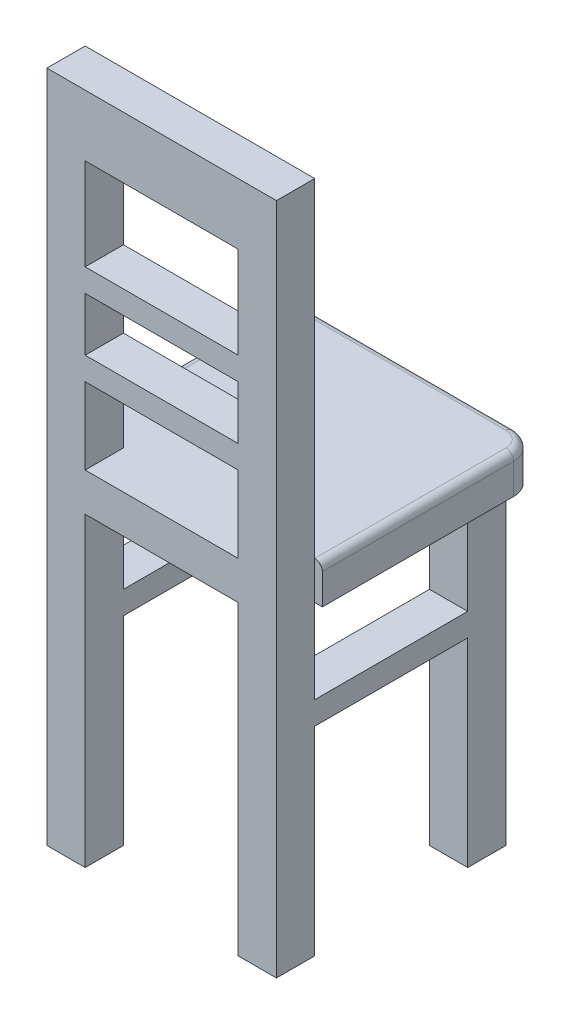
SolidWorks part; units mm, degrees
ref_plane "Front Plane" through (0, 0, 0) normal (0, 0, 1) x (1, 0, 0)
ref_plane "Top Plane" through (0, 0, 0) normal (0, 1, 0) x (1, 0, 0)
ref_plane "Right Plane" through (0, 0, 0) normal (1, 0, 0) x (0, 0, -1)
sketch "Sketch1" plane through (0, 0, 0) normal (0, 1, 0) x (1, 0, 0)
  line L0 (0, 0) -> (-15, 0) construction
  line L1 (-15, 0) -> (-15, 30) construction
  line L2 (-15, 30) -> (0, 30) construction
  line L3 (0, 30) -> (0, 0) construction
  line L4 (-25, 0) -> (-25, 5)
  line L5 (0, 0) -> (-5, 0)
  line L6 (0, 0) -> (0, 5)
  line L7 (0, 5) -> (-5, 5)
  line L8 (-5, 0) -> (-5, 5)
  line L9 (0, 30) -> (-5, 30)
  line L10 (0, 30) -> (0, 25)
  line L11 (0, 25) -> (-5, 25)
  line L12 (-5, 30) -> (-5, 25)
  line L13 (-30, 5) -> (-25, 5)
  line L14 (-30, 0) -> (-30, 5)
  line L15 (-30, 0) -> (-25, 0)
  line L16 (-25, 30) -> (-25, 25)
  line L17 (-30, 25) -> (-25, 25)
  line L18 (-30, 30) -> (-30, 25)
  line L19 (-30, 30) -> (-25, 30)
  dimension "D1" = 5
  dimension "D2" = 5
  dimension "D3" = 5
  dimension "D4" = 5
  dimension "D5" = 30
  dimension "D6" = 15
extrude "Boss-Extrude1" add sketch "Sketch1" along normal blind 40
sketch "Sketch2" plane through (0, 40, 0) normal (0, 1, 0) x (1, 0, 0)
  line L0 (-5, 5) -> (1, 5)
  line L1 (-31, 33) -> (1, 33)
  line L2 (-31, 33) -> (-31, 5)
  line L3 (-31, 5) -> (-25, 5)
  line L4 (1, 33) -> (1, 5)
  line L5 (-5, 0) -> (-25, 0)
  line L6 (-5, 0) -> (-5, 5)
  line L7 (-25, 5) -> (-30, 5) construction
  line L8 (-25, 0) -> (-25, 5)
  line L9 (-25, 30) -> (-30, 30) construction
  line L10 (-30, 30) -> (-30, 25) construction
  line L11 (0, 25) -> (0, 30) construction
  line M2 (-25, 0) -> (-25, 5)
  line M3 (-25, 5) -> (-30, 5)
  dimension "D1" = 0
  dimension "D2" = 3
  dimension "D3" = 1
  dimension "D4" = 1
extrude "Boss-Extrude2" add sketch "Sketch2" along normal blind 5 contours L5 L6 L0 L4 L1 L2 L3 M3 M2
sketch "Sketch3" plane through (0, 40, 0) normal (0, 1, 0) x (1, 0, 0)
  line L1 (-30, 5) -> (-25, 5)
  line L2 (-30, 5) -> (-30, 0)
  line L3 (-30, 0) -> (-25, 0)
  line L4 (-25, 5) -> (-25, 0)
  line L5 (-5, 5) -> (0, 5)
  line L6 (-5, 5) -> (-5, 0)
  line L7 (-5, 0) -> (0, 0)
  line L8 (0, 5) -> (0, 0)
extrude "Boss-Extrude3" add sketch "Sketch3" along normal blind 40
sketch "Sketch4" plane through (0, 80, 0) normal (0, 1, 0) x (1, 0, 0)
  line L1 (-30, 5) -> (0, 5)
  line L2 (-30, 5) -> (-30, 0)
  line L3 (-30, 0) -> (0, 0)
  line L4 (0, 5) -> (0, 0)
extrude "Boss-Extrude4" add sketch "Sketch4" along normal blind 8
sketch "Sketch5" plane through (-25, 0, 0) normal (1, 0, 0) x (0, 0, -1)
  line L0 (5, 45) -> (5, 58) construction
  line L1 (5, 80) -> (5, 45) construction
  line L2 (5, 58) -> (5, 68) construction
  line L3 (0, 80) -> (0, 45) construction
  line L4 (5, 68) -> (0, 68)
  line L5 (5, 68) -> (5, 65)
  line L6 (5, 65) -> (0, 65)
  line L7 (0, 68) -> (0, 65)
  line L9 (5, 58) -> (0, 58)
  line L10 (5, 58) -> (5, 55)
  line L11 (5, 55) -> (0, 55)
  line L12 (0, 58) -> (0, 55)
  dimension "D1" = 13
  dimension "D2" = 10
  dimension "D3" = 3
  dimension "D4" = 3
extrude "Boss-Extrude5" add sketch "Sketch5" along normal blind 20
sketch "Sketch6" plane through (0, 0, -5) normal (0, 0, -1) x (-1, 0, 0)
  line L0 (0, 0) -> (0, 26) construction
  line L1 (0, 40) -> (0, 0) construction
  line L2 (0, 26) -> (30, 26) construction
  line L3 (30, 40) -> (30, 0) construction
  line L4 (5, 40) -> (5, 0) construction
  line L5 (0, 26) -> (5, 26)
  line L6 (0, 26) -> (0, 29)
  line L7 (0, 29) -> (5, 29)
  line L8 (5, 26) -> (5, 29)
  line L9 (25, 40) -> (25, 0) construction
  line L10 (30, 26) -> (25, 26)
  line L11 (30, 26) -> (30, 29)
  line L12 (30, 29) -> (25, 29)
  line L13 (25, 26) -> (25, 29)
  dimension "D1" = 26
  dimension "D2" = 3
  dimension "D3" = 3
extrude "Boss-Extrude6" add sketch "Sketch6" along normal blind 20
fillet "Fillet1" radius 3 2 edges at (-31, 42.5, -33) (1, 42.5, -33)
fillet "Fillet2" radius 1 5 edges at (-31, 45, -17.5) (-30.1213, 45, -32.1213) (-15, 45, -33) (0.1213, 45, -32.1213) (1, 45, -17.5)
